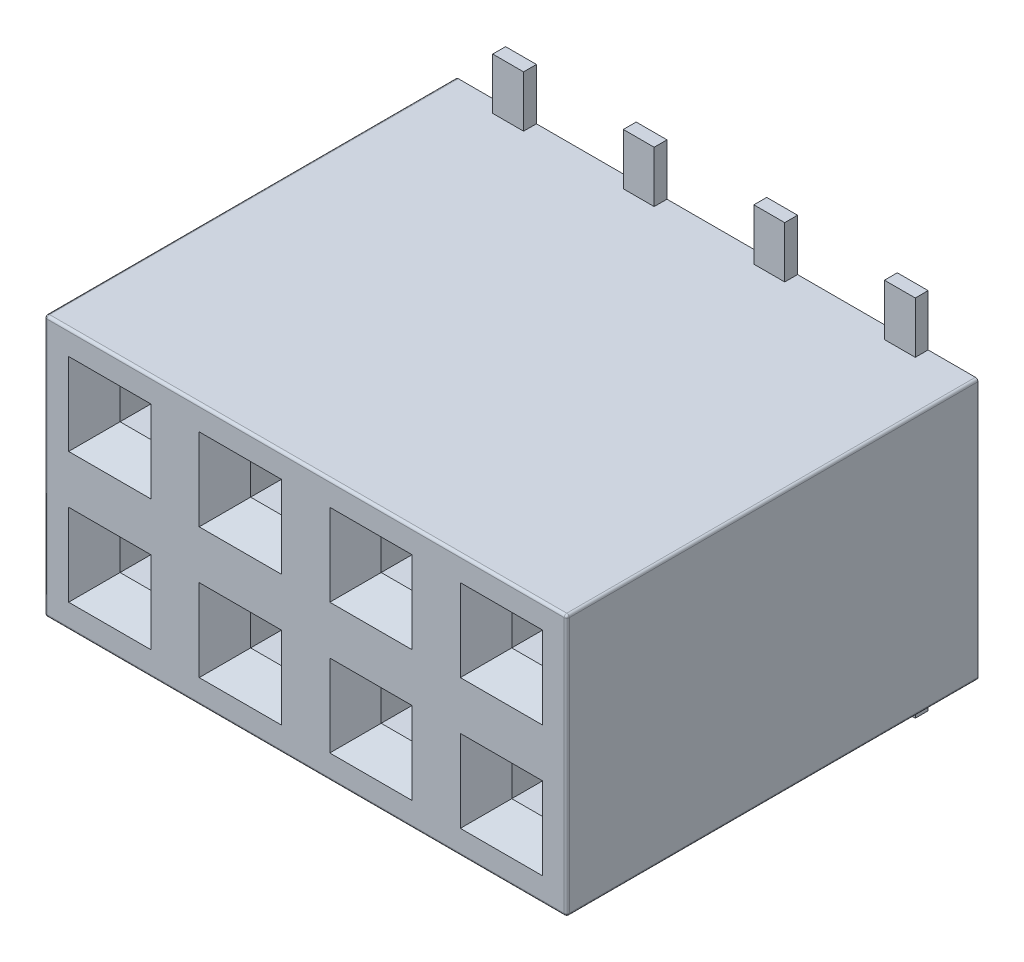
SolidWorks part; units mm, degrees
ref_plane "前视基准面" through (0, 0, 0) normal (0, 0, 1) x (1, 0, 0)
ref_plane "上视基准面" through (0, 0, 0) normal (0, 1, 0) x (1, 0, 0)
ref_plane "右视基准面" through (0, 0, 0) normal (1, 0, 0) x (0, 0, -1)
sketch "草图1" plane through (0, 0, 0) normal (0, 0, 1) x (1, 0, 0)
  line L0 (-1000, 0) -> (49000, 0) construction
  line L1 (0, -1000) -> (0, 49000) construction
  line L2 (-5.08, 2.54) -> (5.08, 2.54)
  line L3 (5.08, 2.54) -> (5.08, -2.54)
  line L4 (-5.08, -2.54) -> (5.08, -2.54)
  line L5 (-5.08, 2.54) -> (-5.08, -2.54)
  point P9 (5.08, 0)
  point P11 (0, -2.54)
  point P12 (0, 2.54)
  dimension "D1" = 10.16
  dimension "D2" = 5.08
extrude "凸台-拉伸1" add sketch "草图1" along normal blind 8
sketch "草图2" plane through (0, 0, 8) normal (0, 0, 1) x (1, 0, 0)
  line L0 (-5.08, 0) -> (5.08, 0) construction
  line L1 (-5.08, 2.54) -> (-5.08, -2.54) construction
  line L2 (5.08, -2.54) -> (5.08, 2.54) construction
  line L3 (0, 2.54) -> (0, -2.54) construction
  line L4 (5.08, 2.54) -> (-5.08, 2.54) construction
  line L5 (-5.08, -2.54) -> (5.08, -2.54) construction
  line L6 (1.57, 0.97) -> (0.97, 0.97)
  line L7 (-0.97, 1.57) -> (-1.57, 1.57)
  line L8 (-0.97, 1.57) -> (-0.97, 0.97)
  line L9 (-0.97, 0.97) -> (-1.57, 0.97)
  line L10 (-1.57, 1.57) -> (-1.57, 0.97)
  line L11 (0.97, 1.57) -> (0.97, 0.97)
  line L12 (1.57, 1.57) -> (0.97, 1.57)
  line L13 (1.57, 1.57) -> (1.57, 0.97)
  line L14 (4.11, 0.97) -> (3.51, 0.97)
  line L15 (3.51, 1.57) -> (3.51, 0.97)
  line L16 (4.11, 1.57) -> (3.51, 1.57)
  line L17 (4.11, 1.57) -> (4.11, 0.97)
  line L18 (-0.97, -1.57) -> (-1.57, -1.57)
  line L19 (-1.57, -0.97) -> (-1.57, -1.57)
  line L20 (-0.97, -0.97) -> (-1.57, -0.97)
  line L21 (-0.97, -0.97) -> (-0.97, -1.57)
  line L22 (1.57, -1.57) -> (0.97, -1.57)
  line L23 (0.97, -0.97) -> (0.97, -1.57)
  line L24 (1.57, -0.97) -> (0.97, -0.97)
  line L25 (1.57, -0.97) -> (1.57, -1.57)
  line L26 (4.11, -1.57) -> (3.51, -1.57)
  line L27 (3.51, -0.97) -> (3.51, -1.57)
  line L28 (4.11, -0.97) -> (3.51, -0.97)
  line L29 (4.11, -0.97) -> (4.11, -1.57)
  line L30 (-4.11, -0.97) -> (-4.11, -1.57)
  line L31 (-4.11, -0.97) -> (-3.51, -0.97)
  line L32 (-3.51, -0.97) -> (-3.51, -1.57)
  line L33 (-4.11, -1.57) -> (-3.51, -1.57)
  line L34 (-4.11, 1.57) -> (-4.11, 0.97)
  line L35 (-4.11, 1.57) -> (-3.51, 1.57)
  line L36 (-3.51, 1.57) -> (-3.51, 0.97)
  line L37 (-4.11, 0.97) -> (-3.51, 0.97)
  circle A0 centre (-1.27, 1.27) radius 0.3 construction
  dimension "D1" = 0.6
  dimension "D2" = 2.54
  dimension "D3" = 2.54
extrude "切除-拉伸1" cut sketch "草图2" against normal through all
chamfer "倒角1" distance 0.5 angle 45 36 edges at (3.51, -1.27, 8) (3.81, -1.57, 8) (4.11, -1.27, 8) (3.81, -0.97, 8) (-3.81, 1.57, 0) (-4.11, 1.27, 0) (-3.51, 1.27, 0) (-3.81, 0.97, 0) (-3.81, -0.97, 0) (-4.11, -1.27, 0) (-3.51, -1.27, 0) (-3.81, -1.57, 0) (-1.57, -1.27, 0) (-1.27, -0.97, 0) (-0.97, -1.27, 0) (-1.27, -1.57, 0) (-1.27, 1.57, 0) (-0.97, 1.27, 0) (-1.27, 0.97, 0) (-1.57, 1.27, 0) (0.97, 1.27, 0) (1.27, 1.57, 0) (1.57, 1.27, 0) (1.27, 0.97, 0) (1.27, -0.97, 0) (0.97, -1.27, 0) (1.27, -1.57, 0) (1.57, -1.27, 0) (3.51, -1.27, 0) (3.81, -0.97, 0) (4.11, -1.27, 0) (3.81, -1.57, 0) (3.51, 1.27, 0) (3.81, 1.57, 0) (4.11, 1.27, 0) (3.81, 0.97, 0)
chamfer "倒角2" distance 0.5 angle 45 28 edges at (3.81, 1.57, 8) (4.11, 1.27, 8) (3.81, 0.97, 8) (3.51, 1.27, 8) (1.57, 1.27, 8) (1.27, 1.57, 8) (0.97, 1.27, 8) (1.27, 0.97, 8) (-0.97, 1.27, 8) (-1.27, 1.57, 8) (-1.27, 0.97, 8) (-1.57, 1.27, 8) (-3.51, 1.27, 8) (-3.81, 1.57, 8) (-3.81, 0.97, 8) (-4.11, 1.27, 8) (-4.11, -1.27, 8) (-3.81, -1.57, 8) (-3.51, -1.27, 8) (-3.81, -0.97, 8) (-0.97, -1.27, 8) (-1.27, -1.57, 8) (-1.57, -1.27, 8) (-1.27, -0.97, 8) (0.97, -1.27, 8) (1.27, -0.97, 8) (1.27, -1.57, 8) (1.57, -1.27, 8)
fillet "圆角1" radius 0.05 8 edges at (-5.08, -2.54, 4) (-5.08, 0, 8) (0, -2.54, 8) (-5.08, 2.54, 4) (0, 2.54, 8) (5.08, 0, 8) (5.08, -2.54, 4) (5.08, 2.54, 4)
sketch "草图4" plane through (0, 2.54, 0) normal (0, 1, 0) x (1, 0, 0)
  line L0 (-4.11, 0) -> (-4.11, -0.25)
  line L1 (-4.11, -0.25) -> (-3.51, -0.25)
  line L2 (-3.51, 0) -> (-3.51, -0.25)
  line L3 (-4.11, 0) -> (-3.51, 0)
  dimension "D1" = 0.25
extrude "凸台-拉伸3" add sketch "草图4" along normal blind 1
pattern_linear "阵列(线性)2" count 4 spacing 2.54 along (1, 0, 0) of "凸台-拉伸3"
mirror "镜向1" about plane through (0, 0, 0) normal (0, 1, 0) of "凸台-拉伸3", "阵列(线性)2"
